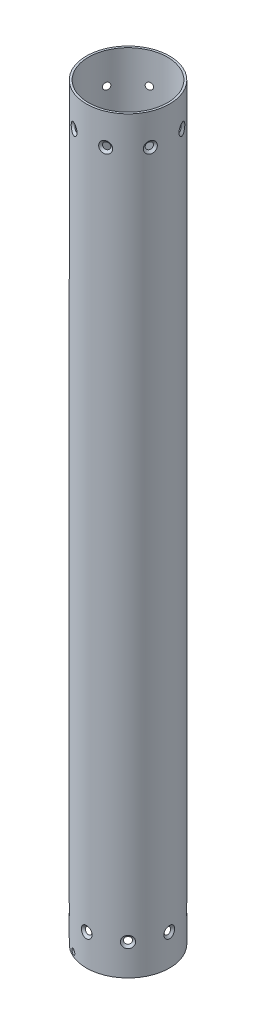
SolidWorks part; units mm, degrees
material "6061-T6 (SS)"
ref_plane "Front Plane" through (0, 0, 0) normal (0, 0, 1) x (1, 0, 0)
ref_plane "Top Plane" through (0, 0, 0) normal (0, 1, 0) x (1, 0, 0)
ref_plane "Right Plane" through (0, 0, 0) normal (1, 0, 0) x (0, 0, -1)
sketch "Sketch1" plane through (0, 0, 0) normal (0, 1, 0) x (1, 0, 0)
  circle A0 centre (0, 0) radius 25.4
  circle A1 centre (0, 0) radius 24.1554
  dimension "D1" = 50.8
  dimension "D2" = 1.2446
extrude "body" add sketch "Sketch1" along normal blind 457.2
hole_wizard "CSK for #6 Flat Head Machine Screw (100) Bottom, front aligned" positions "3DSketch1" profile "Sketch2" countersink size "#6" standard "ANSI Inch"
sketch3d "3DSketch1"
  point P0 (25.4, 19.05, 0)
  dimension "D1" = 19.05
sketch "Sketch2" plane through (25.4, 19.05, 0) normal (0, 1, 0) x (0, 0, -1)
  line L0 (0, 0) -> (0, 4.3158)
  line L1 (0, 4.3158) -> (1.8986, 3.175)
  line L2 (1.8986, 3.175) -> (1.8986, 1.38)
  line L3 (1.8986, 1.38) -> (3.5433, 0)
  line L5 (3.5433, 0) -> (0, 0)
  line L6 (-1.8986, 1.38) -> (-3.5433, 0) construction
  line L10 (0, 4.3158) -> (-1.8986, 3.175) construction
  line L11 (0, -6.35) -> (0, 107.95) construction
  dimension "Hole Dia." = 3.7973
  dimension "Hole Depth" = 3.175
  dimension "Near C'Sink Dia." = 7.0866
  dimension "Near C'Sink Angle" = 100
  dimension "Drill Angle" = 118
pattern_circular "bottom-bolt-pattern" count 8 over 360 about axis through (0, 457.2, 0) along (0, -1, 0) of "CSK for #6 Flat Head Machine Screw (100) Bottom, front aligned"
ref_plane "offset reference" through (9.7202, 0, -23.4665) normal (0.3827, 0, -0.9239) x (0, -1, 0)
hole_wizard "CSK for #6 Flat Head Machine Screw (100) Top, offset" positions "3DSketch3" profile "Sketch4" countersink size "#6" standard "ANSI Inch"
sketch3d "3DSketch3"
  point P0 (9.7202, 438.15, -23.4665)
  dimension "D1" = 19.05
sketch "Sketch4" plane through (9.7202, 438.15, -23.4665) normal (0, 1, 0) x (-0.9239, 0, -0.3827)
  line L0 (0, 0) -> (0, 4.3158)
  line L1 (0, 4.3158) -> (1.8986, 3.175)
  line L2 (1.8986, 3.175) -> (1.8986, 1.38)
  line L3 (1.8986, 1.38) -> (3.5433, 0)
  line L5 (3.5433, 0) -> (0, 0)
  line L6 (-1.8986, 1.38) -> (-3.5433, 0) construction
  line L10 (0, 4.3158) -> (-1.8986, 3.175) construction
  line L11 (0, -6.35) -> (0, 107.95) construction
  dimension "Hole Dia." = 3.7973
  dimension "Hole Depth" = 3.175
  dimension "Near C'Sink Dia." = 7.0866
  dimension "Near C'Sink Angle" = 100
  dimension "Drill Angle" = 118
pattern_circular "top-bolt-pattern" count 8 over 360 about axis through (0, 457.2, 0) along (0, -1, 0) of "CSK for #6 Flat Head Machine Screw (100) Top, offset"
ref_plane "Vent Reference" through (0, 0, 25.4) normal (0, 0, 1) x (1, 0, 0)
hole_wizard "1/8 (0.125) Diameter Hole1" positions "Sketch5" profile "Sketch6" hole size "1/8" standard "ANSI Inch"
sketch "Sketch5" plane through (0, 0, 25.4) normal (0, 0, 1) x (1, 0, 0)
  line L0 (0, 0) -> (-14.2035, 0) construction
  line L1 (-25.4, 0) -> (25.4, 0) construction
  point P0 (-10.16, 2.54)
  dimension "D1" = 2.54
  dimension "D2" = 10.16
sketch "Sketch6" plane through (-10.16, 2.54, 25.4) normal (1, 0, 0) x (0, -1, 0)
  line L0 (0, 0) -> (0, 13.6539)
  line L1 (0, 13.6539) -> (1.5875, 12.7)
  line L2 (1.5875, 12.7) -> (1.5875, 0)
  line L5 (1.5875, 0) -> (0, 0)
  line L10 (0, 13.6539) -> (-1.5875, 12.7) construction
  line L11 (0, -6.35) -> (0, 107.95) construction
  dimension "Hole Dia." = 3.175
  dimension "Hole Depth" = 12.7
  dimension "Drill Angle" = 118
ref_plane "Plane1" through (0, 0, 0) normal (0, 0, 1) x (1, 0, 0)
sketch "Sketch7" plane through (0, 0, 0) normal (0, 0, 1) x (1, 0, 0)
  line L0 (0, 0) -> (0, 456.5653) construction
  line L2 (46.4729, 52.582) -> (-46.8595, 52.582)
  line L3 (46.4729, 52.582) -> (46.4729, 413.2315)
  line L4 (46.4729, 413.2315) -> (-46.8595, 413.2315)
  line L5 (-46.8595, 52.582) -> (-46.8595, 413.2315)
split line "Split Line1"
equation "\"TubeThick\"=0.049"
equation "\"D2@Sketch1\"=\"TubeThick\""
equation "\"Length\"=12"
equation "\"TubeLen\"=12"
